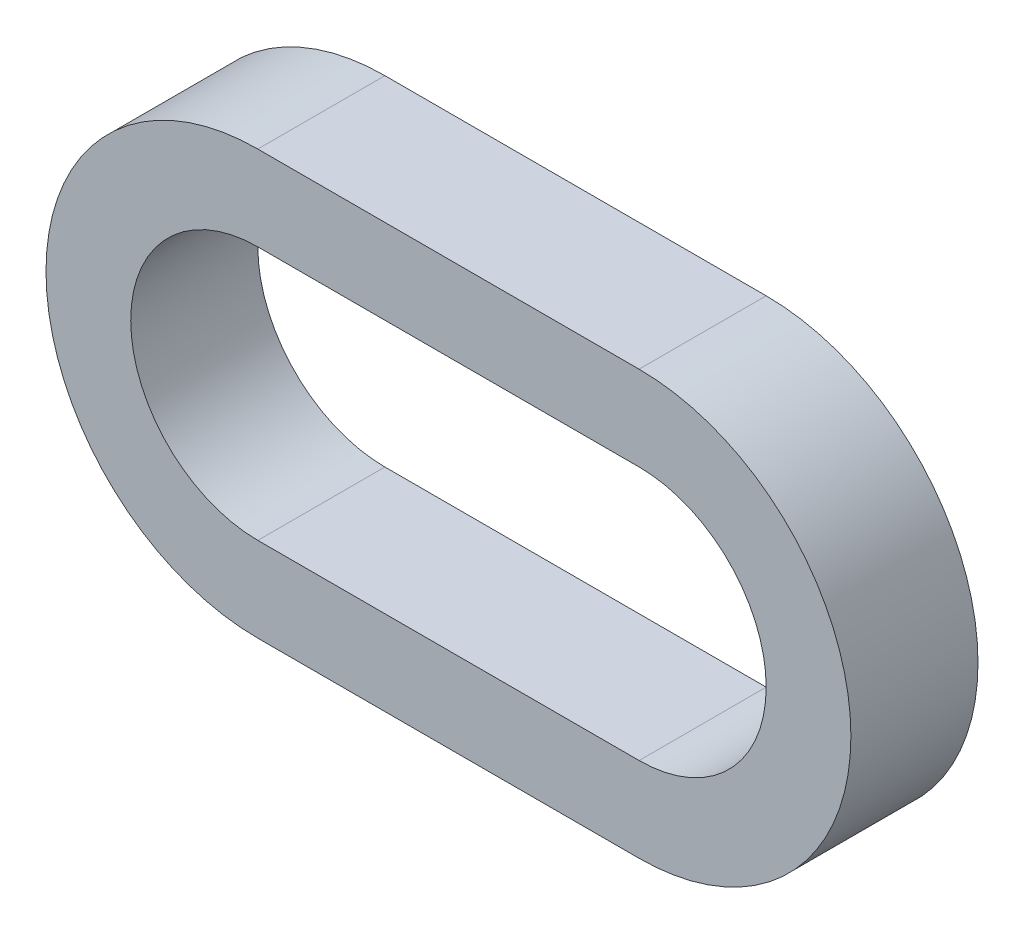
SolidWorks part; units mm, degrees
ref_plane "Front Plane" through (0, 0, 0) normal (0, 0, 1) x (1, 0, 0)
ref_plane "Top Plane" through (0, 0, 0) normal (0, 1, 0) x (1, 0, 0)
ref_plane "Right Plane" through (0, 0, 0) normal (1, 0, 0) x (0, 0, -1)
sketch "Sketch2" plane through (0, 0, 0) normal (0, 0, 1) x (1, 0, 0)
  line L0 (-90, 0) -> (90, 0) construction
  line L1 (-90, 100) -> (90, 100)
  line L2 (-90, -100) -> (90, -100)
  line L3 (-90, 60) -> (90, 60)
  line L4 (-90, -60) -> (90, -60)
  arc A0 (-90, 100) -> (-90, -100) centre (-90, 0) ccw
  arc A1 (90, -100) -> (90, 100) centre (90, 0) ccw
  arc A2 (90, -60) -> (90, 60) centre (90, 0) ccw
  arc A3 (-90, 60) -> (-90, -60) centre (-90, 0) ccw
  point P2 (0, 0)
  point P8 (-190, 0)
  point P9 (190, 0)
  dimension "D1" = 380
  dimension "D2" = 200
  dimension "D3" = 40
extrude "Boss-Extrude1" add sketch "Sketch2" along normal blind 60
